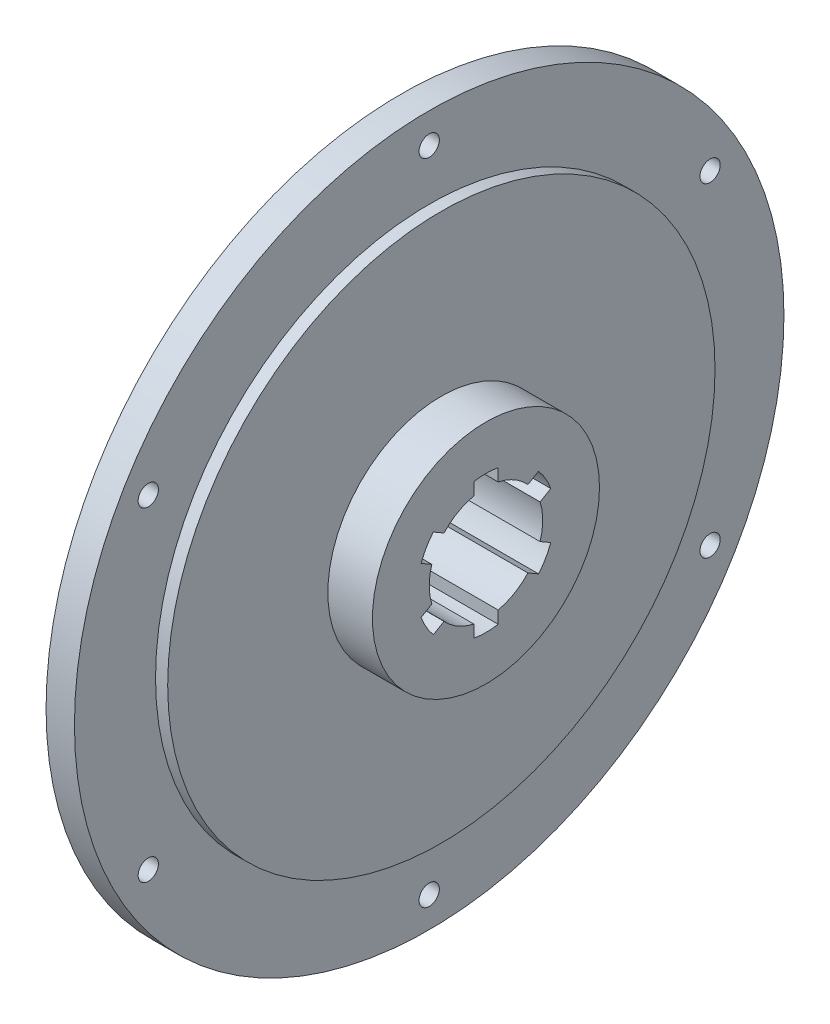
SolidWorks part; units mm, degrees
material "1023 Carbon Steel Sheet (SS)"
ref_plane "Front Plane" through (0, 0, 0) normal (0, 0, 1) x (1, 0, 0)
ref_plane "Top Plane" through (0, 0, 0) normal (0, 1, 0) x (1, 0, 0)
ref_plane "Right Plane" through (0, 0, 0) normal (1, 0, 0) x (0, 0, -1)
sketch "Sketch1" plane through (0, 0, 0) normal (1, 0, 0) x (0, 0, -1)
  circle A0 centre (0, 0) radius 87.5
  dimension "D1" = 175
extrude "Boss-Extrude1" add sketch "Sketch1" along normal blind 7
sketch "Sketch2" plane through (7, 0, 0) normal (1, 0, 0) x (0, 0, -1)
  circle A0 centre (0, 0) radius 67.5
  dimension "D1" = 135
extrude "Boss-Extrude2" add sketch "Sketch2" along normal blind 3
sketch "Sketch3" plane through (7, 0, 0) normal (1, 0, 0) x (0, 0, -1)
  circle A0 centre (0, 0) radius 80 construction
  circle A2 centre (0, -80) radius 2.5
  circle A3 centre (-69.282, -40) radius 2.5
  circle A4 centre (-69.282, 40) radius 2.5
  circle A5 centre (0, 80) radius 2.5
  circle A6 centre (69.282, 40) radius 2.5
  circle A7 centre (69.282, -40) radius 2.5
  point P18 (0, 0)
  dimension "D1" = 160
  dimension "D2" = 5
  dimension "D3" = 6
extrude "Cut-Extrude1" cut sketch "Sketch3" against normal through all
sketch "Sketch4" plane through (10, 0, 0) normal (1, 0, 0) x (0, 0, -1)
  circle A0 centre (0, 0) radius 28
  dimension "D1" = 56
extrude "Boss-Extrude3" add sketch "Sketch4" along normal blind 11 contours A0
sketch "Sketch6" plane through (0, 0, 0) normal (-1, 0, 0) x (0, 0, 1)
  circle A0 centre (0, 0) radius 28
  dimension "D1" = 56
extrude "Boss-Extrude4" add sketch "Sketch6" along normal blind 11
sketch "Sketch8" plane through (21, 0, 0) normal (1, 0, 0) x (0, 0, -1)
  line L0 (0, -1000) -> (0, 49000) construction
  line L2 (-3, 16.7332) -> (-3, 13.6748)
  line L4 (3, 16.7332) -> (3, 13.6748)
  line L5 (-3, 16.7332) -> (3, 13.6748) construction
  line L6 (-3, 13.6748) -> (3, 16.7332) construction
  line L7 (12.9914, 10.9647) -> (10.3427, 9.4355)
  line L8 (15.9914, 5.7685) -> (13.3427, 4.2393)
  line L9 (15.9914, -5.7685) -> (13.3427, -4.2393)
  line L10 (12.9914, -10.9647) -> (10.3427, -9.4355)
  line L11 (3, -16.7332) -> (3, -13.6748)
  line L12 (-3, -16.7332) -> (-3, -13.6748)
  line L13 (-12.9914, -10.9647) -> (-10.3427, -9.4355)
  line L14 (-15.9914, -5.7685) -> (-13.3427, -4.2393)
  line L15 (-15.9914, 5.7685) -> (-13.3427, 4.2393)
  line L16 (-12.9914, 10.9647) -> (-10.3427, 9.4355)
  arc A0 (-12.9914, 10.9647) -> (-15.9914, 5.7685) centre (0, 0) ccw
  arc A1 (-3, 13.6748) -> (-10.3427, 9.4355) centre (0, 0) ccw
  arc A2 (3, 16.7332) -> (-3, 16.7332) centre (0, 0) ccw
  arc A3 (10.3427, 9.4355) -> (3, 13.6748) centre (0, 0) ccw
  arc A4 (15.9914, 5.7685) -> (12.9914, 10.9647) centre (0, 0) ccw
  arc A5 (13.3427, -4.2393) -> (13.3427, 4.2393) centre (0, 0) ccw
  arc A6 (12.9914, -10.9647) -> (15.9914, -5.7685) centre (0, 0) ccw
  arc A7 (3, -13.6748) -> (10.3427, -9.4355) centre (0, 0) ccw
  arc A8 (-3, -16.7332) -> (3, -16.7332) centre (0, 0) ccw
  arc A9 (-15.9914, -5.7685) -> (-12.9914, -10.9647) centre (0, 0) ccw
  arc A10 (-10.3427, -9.4355) -> (-3, -13.6748) centre (0, 0) ccw
  arc A11 (-13.3427, 4.2393) -> (-13.3427, -4.2393) centre (0, 0) ccw
  point P4 (0, 15.204)
  point P34 (0, 0)
  dimension "D1" = 28
  dimension "D2" = 34
  dimension "D3" = 6
  dimension "D4" = 6
extrude "Cut-Extrude2" cut sketch "Sketch8" against normal through all
